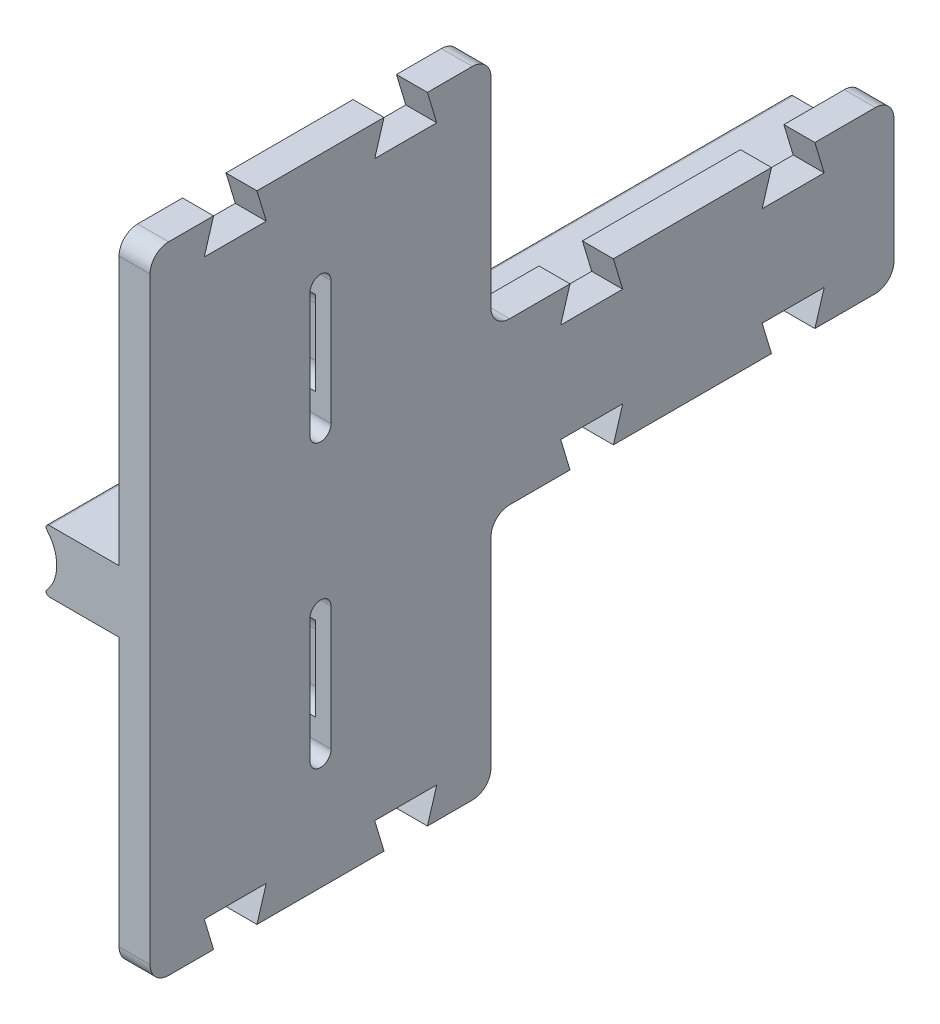
SolidWorks part; units mm, degrees
material "ABS"
ref_plane "Front Plane" through (0, 0, 0) normal (0, 0, 1) x (1, 0, 0)
ref_plane "Top Plane" through (0, 0, 0) normal (0, 1, 0) x (1, 0, 0)
ref_plane "Right Plane" through (0, 0, 0) normal (1, 0, 0) x (0, 0, -1)
sketch "Sketch1" plane through (0, 0, 0) normal (1, 0, 0) x (0, 0, -1)
  line L0 (0, 39.25) -> (0, 6.25) construction
  line L1 (-27.5, -39.25) -> (27.5, -39.25)
  line L2 (-27.5, -39.25) -> (-27.5, 39.25)
  line L4 (27.5, -39.25) -> (27.5, 39.25)
  line L5 (-27.5, -39.25) -> (27.5, 39.25) construction
  line L6 (-27.5, 39.25) -> (27.5, -39.25) construction
  line L7 (-27.5, -6.25) -> (27.5, -6.25) construction
  line L8 (-27.5, -6.25) -> (-27.5, 6.25) construction
  line L9 (-27.5, 6.25) -> (27.5, 6.25) construction
  line L10 (27.5, -6.25) -> (27.5, 6.25) construction
  line L11 (-27.5, -6.25) -> (27.5, 6.25) construction
  line L12 (-27.5, 6.25) -> (27.5, -6.25) construction
  line L13 (-27.5, 6.25) -> (27.5, 6.25) construction
  line L14 (-27.5, 6.25) -> (-27.5, 39.25) construction
  line L16 (27.5, 6.25) -> (27.5, 39.25) construction
  line L17 (-27.5, 39.25) -> (27.5, 39.25)
  line L18 (-27.5, 0) -> (27.5, 0) construction
  line L19 (0, -32.75) -> (0, -12.75) construction
  line L22 (-1.7, -32.75) -> (-1.7, -12.75)
  line L23 (1.7, -32.75) -> (1.7, -12.75)
  line L24 (0, 32.75) -> (0, 12.75) construction
  line L25 (-1.7, 32.75) -> (-1.7, 12.75)
  line L26 (1.7, 32.75) -> (1.7, 12.75)
  arc A6 (-1.7, -32.75) -> (1.7, -32.75) centre (0, -32.75) ccw
  arc A7 (1.7, -12.75) -> (-1.7, -12.75) centre (0, -12.75) ccw
  arc A8 (-1.7, 32.75) -> (1.7, 32.75) centre (0, 32.75) cw
  arc A9 (1.7, 12.75) -> (-1.7, 12.75) centre (0, 12.75) cw
  point P1 (0, 0)
  point P6 (0, 0)
  point P16 (0, 22.75)
  point P17 (0, 14.75)
  point P18 (0, 30.75)
  point P20 (0, -22.75)
  point P21 (0, -22.75)
  point P30 (0, 22.75)
  dimension "D4" = 8
  dimension "D6" = 1.7
  dimension "D1" = 55
  dimension "D2" = 12.5
  dimension "D3" = 33
  dimension "D5" = 8
  dimension "D7" = 20
extrude "Boss-Extrude1" add sketch "Sketch1" along normal mid plane 5
hole_wizard "M3 Clearance Hole1" positions "Sketch4" profile "Sketch5" hole size "M3" standard "ANSI Metric"
sketch "Sketch4" plane through (-2.5, 0, 0) normal (-1, 0, 0) x (0, 0, 1)
  point P0 (0, 30.75)
  point P7 (0, 14.75)
sketch "Sketch5" plane through (-2.5, 30.75, 0) normal (0, 1, 0) x (0, 0, 1)
  line L0 (0, 0) -> (0, 5)
  line L1 (0, 5) -> (1.6, 5)
  line L2 (1.6, 5) -> (1.6, 0.125)
  line L3 (1.6, 0.125) -> (1.725, 0)
  line L5 (1.725, 0) -> (0, 0)
  line L6 (-1.6, 0.125) -> (-1.725, 0) construction
  line L11 (0, -6.35) -> (0, 107.95) construction
  dimension "Thru Hole Dia." = 3.2
  dimension "Thru Hole Depth" = 5
  dimension "Near C'Sink Dia." = 3.45
  dimension "Near C'Sink Angle" = 90
sketch "Sketch6" plane through (-2.5, 0, 0) normal (-1, 0, 0) x (0, 0, 1)
  line L0 (27.5, -39.25) -> (27.5, 39.25) construction
  line L1 (-27.5, -5) -> (27.5, -5)
  line L2 (-27.5, -5) -> (-27.5, 5)
  line L3 (-27.5, 5) -> (27.5, 5)
  line L4 (27.5, -5) -> (27.5, 5)
  line L5 (-27.5, -5) -> (27.5, 5) construction
  line L6 (-27.5, 5) -> (27.5, -5) construction
  point P0 (0, 0)
  dimension "D1" = 10
extrude "Boss-Extrude2" add sketch "Sketch6" along normal blind 16.3
sketch "Sketch7" plane through (0, 0, 27.5) normal (0, 0, 1) x (1, 0, 0)
  line L0 (-18.8, -5) -> (-18.8, 5) construction
  line L1 (-18.8, -5) -> (-2.5, -5) construction
  line L2 (-18.8, 5) -> (-2.5, 5) construction
  line L4 (-15.05, 5) -> (-18.8, 5)
  line L6 (-15.05, -5) -> (-18.8, -5)
  line L7 (-18.8, 5) -> (-18.8, -5)
  arc A0 (-15.05, -5) -> (-15.05, 5) centre (-18.8, 0) ccw
  dimension "D1" = 6.25
extrude "Cut-Extrude1" cut sketch "Sketch7" against normal through all
sketch "Sketch9" plane through (-2.5, 0, 0) normal (-1, 0, 0) x (0, 0, 1)
  line L8 (0, 0) -> (42.0161, 0) construction
  line L11 (27.5, 39.25) -> (-27.5, 39.25)
  line L14 (27.5, 39.25) -> (27.5, 51.25)
  line L19 (-27.5, 39.25) -> (-27.5, 51.25)
  line L21 (27.5, 51.25) -> (-27.5, 51.25)
  dimension "D1" = 12
extrude "Boss-Extrude3" add sketch "Sketch9" against normal up to surface (5 mm away) up to face at (2.5, 0, 0)
sketch "Sketch16" plane through (-2.5, 0, 0) normal (-1, 0, 0) x (0, 0, 1)
  line L1 (27.5, 51.25) -> (-27.5, 51.25) construction
  line L4 (10.25, 51.25) -> (17.25, 51.25)
  line L6 (17.25, 51.25) -> (18.75, 46.25)
  line L7 (18.75, 46.25) -> (8.75, 46.25)
  line L8 (8.75, 46.25) -> (10.25, 51.25)
  line L9 (0, 51.25) -> (0, 39.25) construction
  line L10 (0, 51.25) -> (27.5, 51.25) construction
  line L11 (-18.75, 46.25) -> (-8.75, 46.25)
  line L12 (-17.25, 51.25) -> (-18.75, 46.25)
  line L13 (-10.25, 51.25) -> (-17.25, 51.25)
  line L14 (-8.75, 46.25) -> (-10.25, 51.25)
  point P1 (0, 51.25)
  point P15 (13.75, 51.25)
  point P16 (13.75, 51.25)
  dimension "D1" = 7
  dimension "D2" = 5
  dimension "D3" = 10
extrude "Cut-Extrude4" cut sketch "Sketch16" against normal up to surface (5 mm away)
mirror "Mirror1" about plane through (0, 0, 0) normal (0, 1, 0) of "Boss-Extrude3"
sketch "Sketch10" plane through (0, 0, 0) normal (1, 0, 0) x (0, 0, -1)
  line L0 (0, -18.75) -> (0, -26.75) construction
  line L1 (0, -32.75) -> (0, -12.75) construction
  line L2 (3.25, -18.75) -> (3.25, -26.75)
  line L3 (-3.25, -18.75) -> (-3.25, -26.75)
  line L4 (27.5, 0) -> (-27.5, 0) construction
  line L5 (0, 18.75) -> (0, 26.75) construction
  line L6 (3.25, 18.75) -> (3.25, 26.75)
  line L7 (-3.25, 18.75) -> (-3.25, 26.75)
  circle A0 centre (0, 22.75) radius 3.25 construction
  arc A1 (3.25, -18.75) -> (-3.25, -18.75) centre (0, -18.75) ccw
  arc A2 (-3.25, -26.75) -> (3.25, -26.75) centre (0, -26.75) ccw
  arc A3 (3.25, 18.75) -> (-3.25, 18.75) centre (0, 18.75) cw
  arc A4 (-3.25, 26.75) -> (3.25, 26.75) centre (0, 26.75) cw
  point P8 (0, -22.75)
  point P19 (0, 22.75)
  dimension "D1" = 6.5
  dimension "D2" = 3.25
  dimension "D3" = 8
extrude "Cut-Extrude2" cut sketch "Sketch10" against normal up to surface (2.5 mm away) up to face at (-2.5, 22.75, 0)
sketch "Sketch11" plane through (0, 0, -27.5) normal (0, 0, -1) x (-1, 0, 0)
  line L0 (2.5, 5) -> (2.5, 51.25) construction
  line L1 (-2.5, -13) -> (2.5, -13)
  line L2 (-2.5, -13) -> (-2.5, 13)
  line L3 (-2.5, 13) -> (2.5, 13)
  line L4 (2.5, -13) -> (2.5, -5)
  line L5 (-2.5, -13) -> (2.5, 13) construction
  line L6 (-2.5, 13) -> (2.5, -13) construction
  line L8 (2.5, 5) -> (15.05, 5)
  line L10 (2.5, -5) -> (15.05, -5)
  line L12 (2.5, 5) -> (2.5, 13)
  arc A0 (15.05, 5) -> (15.05, -5) centre (18.8, 0) ccw
  arc A1 (15.05, 5) -> (15.05, -5) centre (18.8, 0) ccw construction
  point P0 (0, 0)
  dimension "D1" = 8
extrude "Boss-Extrude4" add sketch "Sketch11" along normal blind 65
fillet "Fillet1" radius 0.5 2 edges at (-15.05, -5, -32.5) (-15.05, 5, -32.5)
sketch "Sketch15" plane through (-2.5, 0, 0) normal (-1, 0, 0) x (0, 0, 1)
  line L0 (-40.25, 13) -> (-38.75, 8)
  line L1 (-92.5, 13) -> (-27.5, 13) construction
  line L2 (-38.75, 8) -> (-48.75, 8)
  line L3 (-48.75, 8) -> (-47.25, 13)
  line L4 (-47.25, 13) -> (-40.25, 13)
  line L5 (-60, 13) -> (-27.5, 13) construction
  line L6 (-60, 13) -> (-92.5, 13) construction
  line L7 (-60, 13) -> (-60, 5) construction
  line L8 (-92.5, 5) -> (27.5, 5) construction
  line L9 (-72.75, 13) -> (-79.75, 13)
  line L10 (-81.25, 8) -> (-71.25, 8)
  line L11 (-79.75, 13) -> (-81.25, 8)
  line L12 (-71.25, 8) -> (-72.75, 13)
  point P7 (-60, 13)
  point P13 (-43.75, 13)
  point P14 (-43.75, 13)
  dimension "D1" = 7
  dimension "D2" = 10
  dimension "D3" = 5
extrude "Cut-Extrude3" cut sketch "Sketch15" against normal up to surface (5 mm away) up to face at (2.5, 24.375, -15)
mirror "Mirror2" about plane through (0, 0, 0) normal (0, 1, 0) of "Cut-Extrude3"
mirror "Mirror3" about plane through (0, 0, 0) normal (0, 1, 0) of "Cut-Extrude4"
fillet "Fillet2" radius 3 8 edges at (0, -51.25, 27.5) (0, -51.25, -27.5) (0, 13, -27.5) (0, -13, -27.5) (0, 13, -92.5) (0, -13, -92.5) (0, 51.25, -27.5) (0, 51.25, 27.5)
